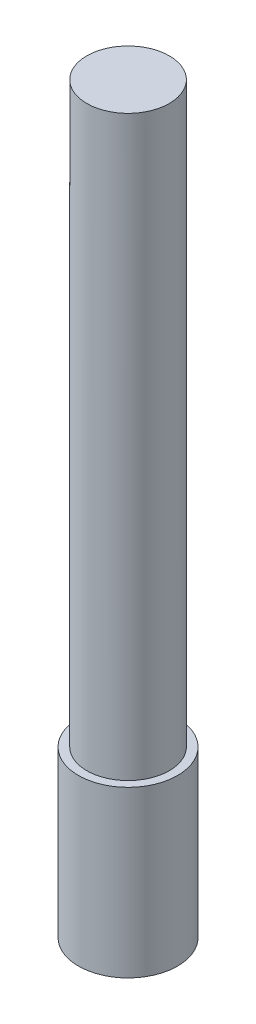
SolidWorks part; units mm, degrees
ref_plane "Front Plane" through (0, 0, 0) normal (0, 0, 1) x (1, 0, 0)
ref_plane "Top Plane" through (0, 0, 0) normal (0, 1, 0) x (1, 0, 0)
ref_plane "Right Plane" through (0, 0, 0) normal (1, 0, 0) x (0, 0, -1)
sketch "Sketch1" plane through (0, 0, 0) normal (0, 1, 0) x (1, 0, 0)
  circle A0 centre (0, 0) radius 0.5
  dimension "D1" = 1
sketch "Sketch2" plane through (0, 0, 0) normal (1, 0, 0) x (0, 0, -1)
  line L0 (0, 0) -> (0, -9)
  dimension "D1" = 9
sweep "Sweep1" add profiles "Sketch1" path "Sketch2"
sketch "Sketch3" plane through (0, -9, 0) normal (0, -1, 0) x (1, 0, 0)
  circle A0 centre (0, 0) radius 0.6
  dimension "D1" = 1.2
extrude "Boss-Extrude1" add sketch "Sketch3" against normal blind 2
